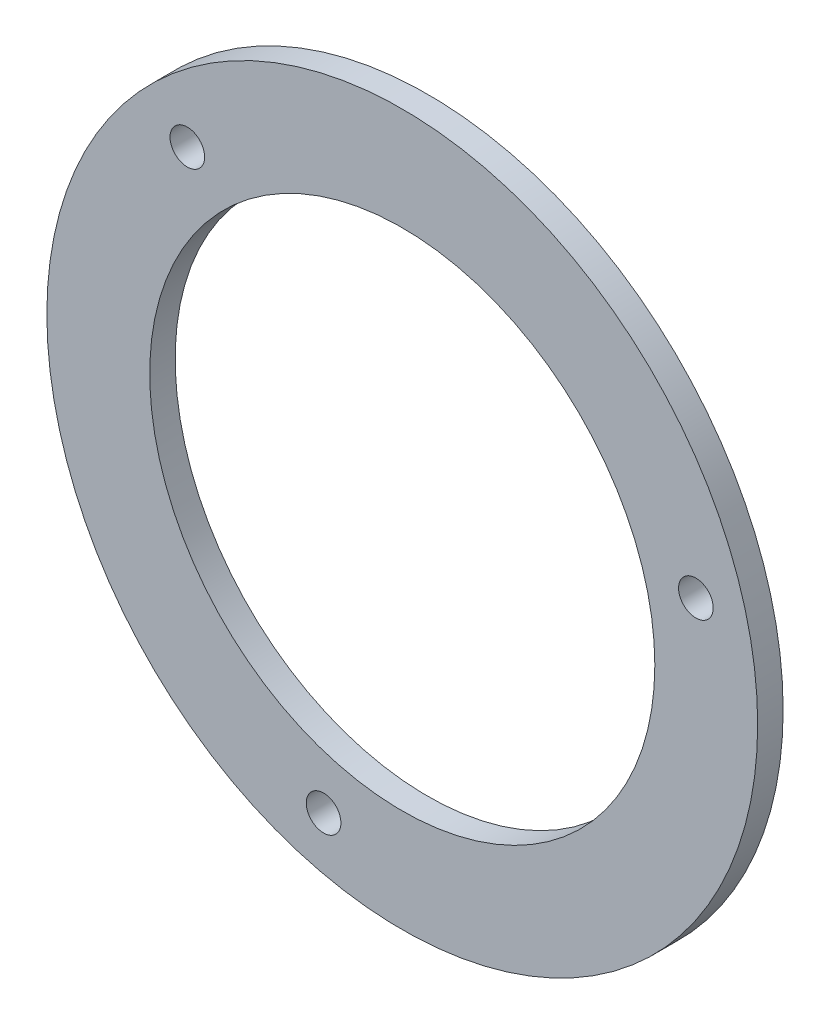
SolidWorks part; units mm, degrees
ref_plane "Front Plane" through (0, 0, 0) normal (0, 0, 1) x (1, 0, 0)
ref_plane "Top Plane" through (0, 0, 0) normal (0, 1, 0) x (1, 0, 0)
ref_plane "Right Plane" through (0, 0, 0) normal (1, 0, 0) x (0, 0, -1)
sketch "S01 - TPU bead and bearing outer-race keeper" plane through (0, 0, 0) normal (0, 0, 1) x (1, 0, 0)
  circle A0 centre (0, 0) radius 34.9
  circle A1 centre (0, 0) radius 24.8
  dimension "D1" = 49.6
  dimension "D2" = 69.8
extrude "01 - TPU bead and bearing outer-race keeper" add sketch "S01 - TPU bead and bearing outer-race keeper" along normal blind 2.5
sketch "S02 - Flange screw clearance" plane through (0, 0, 0) normal (0, 0, 1) x (1, 0, 0)
  circle A0 centre (28.8329, 7.7257) radius 1.7
  circle A1 centre (-21.1071, 21.1071) radius 1.7
  circle A2 centre (-7.7257, -28.8329) radius 1.7
  dimension "D1" = 3.4
  dimension "D2" = 3.4
  dimension "D3" = 3.4
  dimension "D4" = 28.8329
  dimension "D5" = 7.7257
  dimension "D6" = 21.1071
  dimension "D7" = 7.7257
  dimension "D8" = 21.1071
  dimension "D9" = 28.8329
extrude "02 - Flange screw clearance" cut sketch "S02 - Flange screw clearance" along normal blind 2.7 from offset 0.1
